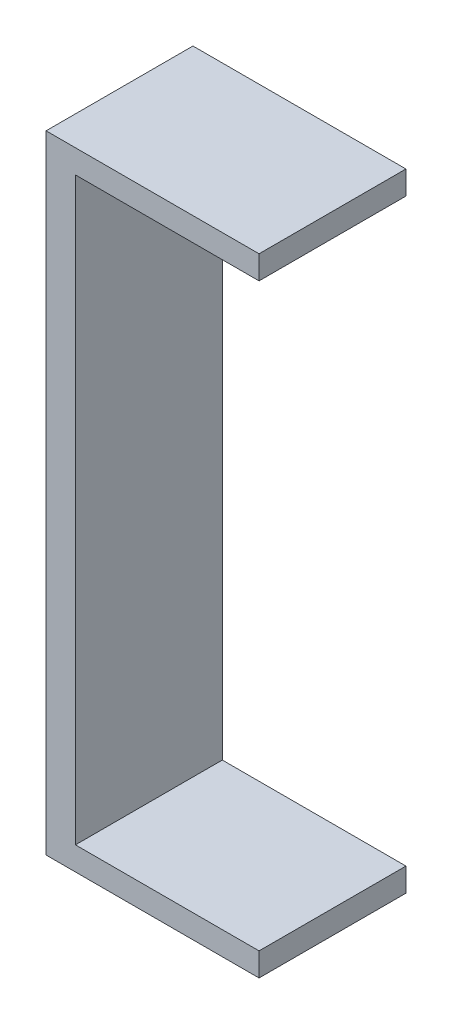
SolidWorks part; units mm, degrees
ref_plane "Front Plane" through (0, 0, 0) normal (0, 0, 1) x (1, 0, 0)
ref_plane "Top Plane" through (0, 0, 0) normal (0, 1, 0) x (1, 0, 0)
ref_plane "Right Plane" through (0, 0, 0) normal (1, 0, 0) x (0, 0, -1)
sketch "Sketch1" plane through (0, 0, 0) normal (0, 0, 1) x (1, 0, 0)
  line L0 (18.415, 54.229) -> (0, 54.229)
  line L1 (0, 54.229) -> (0, 0)
  line L2 (0, 0) -> (18.415, 0)
  line L3 (18.415, 0) -> (18.415, 2.032)
  line L4 (18.415, 2.032) -> (2.54, 2.032)
  line L5 (2.54, 2.032) -> (2.54, 52.197)
  line L6 (2.54, 52.197) -> (18.415, 52.197)
  line L7 (18.415, 52.197) -> (18.415, 54.229)
  dimension "D1" = 2.54
  dimension "D2" = 2.032
  dimension "D3" = 2.032
  dimension "D4" = 50.165
  dimension "D5" = 15.875
extrude "Boss-Extrude1" add sketch "Sketch1" along normal blind 12.7
